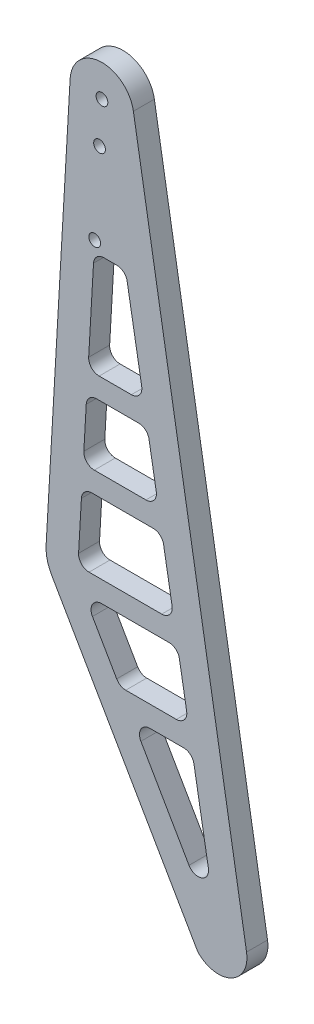
SolidWorks part; units mm, degrees
ref_plane "Front Plane" through (0, 0, 0) normal (0, 0, 1) x (1, 0, 0)
ref_plane "Top Plane" through (0, 0, 0) normal (0, 1, 0) x (1, 0, 0)
ref_plane "Right Plane" through (0, 0, 0) normal (1, 0, 0) x (0, 0, -1)
sketch "Sketch1" plane through (0, 0, 0) normal (0, 0, 1) x (1, 0, 0)
  line L0 (0, 0) -> (3.7296, 64.5742) construction
  line L1 (0, 0) -> (60.5725, 0) construction
  line L2 (-4.836, 0) -> (18.2506, -39.9872)
  line L3 (0, 0) -> (21.3768, -37.0258) construction
  line L4 (-1.0903, 64.8526) -> (-4.836, 0)
  line L8 (8.4905, 65.3764) -> (25.6232, -36.3103)
  arc A0 (18.2506, -39.9872) -> (25.6232, -36.3103) centre (21.3768, -37.0258) ccw
  arc A1 (-1.0903, 64.8526) -> (8.4905, 65.3764) centre (3.7296, 64.5742) cw
  point P6 (3.3635, 58.2348)
  point P8 (2.6312, 45.5559)
  dimension "D4" = 60
  dimension "D8" = 101.6
  dimension "D1" = 6.35
  dimension "D3" = 12.7
extrude "Boss-Extrude1" add sketch "Sketch1" along normal blind 3.175
fillet "Fillet1" radius 6.35 1 edges at (-4.836, 0, 1.5875)
hole_wizard "#2-56 Tapped Hole2" positions "3DSketch3" profile "Sketch4" tap size "#2-56" standard "ANSI Inch" end condition through all
sketch3d "3DSketch3"
  point P0 (2.6312, 45.5559, 3.175)
  point P2 (3.3635, 58.2348, 3.175)
  point P4 (3.7296, 64.5742, 3.175)
sketch "Sketch4" plane through (2.6312, 45.5559, 3.175) normal (1, 0, 0) x (0, -1, 0)
  line L0 (0, 0) -> (0, 3.175)
  line L1 (0, 3.175) -> (0.889, 3.175)
  line L2 (0.889, 3.175) -> (0.889, 0)
  line L5 (0.889, 0) -> (0, 0)
  line L11 (0, -6.35) -> (0, 107.95) construction
  dimension "Thru Tap Drill Dia." = 1.778
  dimension "Thru Tap Drill Depth" = 3.175
cosmetic thread "Hole Thread3" parameters "D2"=2.1844
cosmetic thread "Hole Thread4" parameters "D2"=2.1844
cosmetic thread "Hole Thread5" parameters "D2"=2.1844
sketch "Sketch5" plane through (0, 0, 3.175) normal (0, 0, 1) x (1, 0, 0)
  line L0 (0, 0) -> (3.7296, 64.5742) construction
  line L1 (0, 0) -> (3.7296, 64.5742) construction
  line L2 (0, 0) -> (21.3768, -37.0258) construction
  line L3 (3.7296, 64.5742) -> (21.3768, -37.0258) construction
  line L4 (2.5377, 43.9367) -> (7.3142, 43.9367)
  line L5 (0, 0) -> (14.9457, 0) construction
  line L6 (0, 0) -> (60.5725, 0) construction
  line L7 (7.3323, -12.7) -> (17.1516, -12.7) construction
  line L8 (0.7956, 13.7742) -> (12.5532, 13.7742) construction
  line L9 (1.5291, 26.4742) -> (10.3473, 26.4742) construction
  line L10 (2.6294, 45.5242) -> (7.0385, 45.5242) construction
  line L11 (7.3142, 43.9367) -> (10.0716, 28.0617)
  line L12 (10.0716, 28.0617) -> (1.6208, 28.0617)
  line L13 (1.6208, 28.0617) -> (2.5377, 43.9367)
  line L14 (1.4374, 24.8867) -> (10.6231, 24.8867)
  line L15 (10.6231, 24.8867) -> (12.2775, 15.3617)
  line L16 (12.2775, 15.3617) -> (0.8873, 15.3617)
  line L17 (0.8873, 15.3617) -> (1.4374, 24.8867)
  line L18 (0.7039, 12.1867) -> (12.829, 12.1867)
  line L19 (12.829, 12.1867) -> (14.67, 1.5875)
  line L20 (14.67, 1.5875) -> (0.0917, 1.5875)
  line L21 (0.0917, 1.5875) -> (0.7039, 12.1867)
  line L22 (0.9165, -1.5875) -> (15.2215, -1.5875)
  line L23 (15.2215, -1.5875) -> (16.8759, -11.1125)
  line L24 (16.8759, -11.1125) -> (6.4158, -11.1125)
  line L25 (6.4158, -11.1125) -> (0.9165, -1.5875)
  line L26 (21.3768, -37.0258) -> (17.4274, -14.2875)
  line L27 (17.4274, -14.2875) -> (8.2489, -14.2875)
  line L28 (8.2489, -14.2875) -> (21.3768, -37.0258)
  point P33 (30.2314, -30.2314)
  point P39 (31.1265, -32.6071)
  dimension "D1" = 19.05
  dimension "D2" = 19.05
  dimension "D3" = 12.7
  dimension "D4" = 12.7
  dimension "D5" = 1.5875
  dimension "D6" = 1.5875
  dimension "D7" = 1.5875
  dimension "D8" = 1.5875
  dimension "D9" = 1.5875
  dimension "D10" = 1.5875
  dimension "D11" = 1.5875
  dimension "D12" = 1.5875
  dimension "D13" = 1.5875
extrude "Cut-Extrude1" cut sketch "Sketch5" against normal through all
fillet "Fillet2" radius 1.5875 19 edges at (10.0716, 28.0617, 1.5875) (2.5377, 43.9367, 1.5875) (7.3142, 43.9367, 1.5875) (12.829, 12.1867, 1.5875) (14.67, 1.5875, 1.5875) (12.2775, 15.3617, 1.5875) (10.6231, 24.8867, 1.5875) (1.4374, 24.8867, 1.5875) (0.7039, 12.1867, 1.5875) (8.2489, -14.2875, 1.5875) (21.3768, -37.0258, 1.5875) (16.8759, -11.1125, 1.5875) (0.9165, -1.5875, 1.5875) (15.2215, -1.5875, 1.5875) (17.4274, -14.2875, 1.5875) (6.4158, -11.1125, 1.5875) (0.0917, 1.5875, 1.5875) (0.8873, 15.3617, 1.5875) (1.6208, 28.0617, 1.5875)
